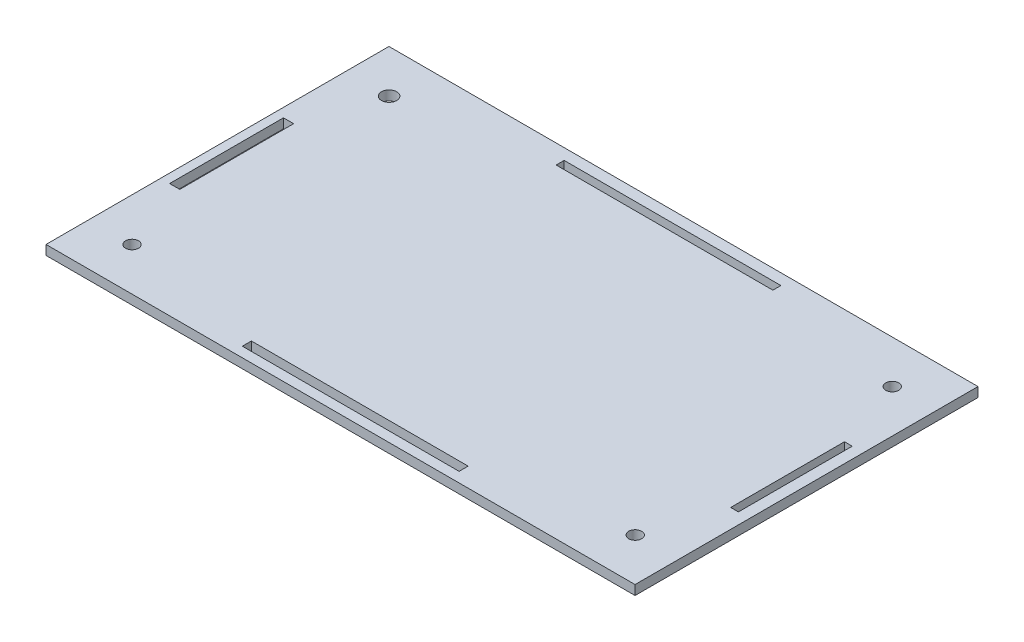
SolidWorks part; units mm, degrees
ref_plane "Front Plane" through (0, 0, 0) normal (0, 0, 1) x (1, 0, 0)
ref_plane "Top Plane" through (0, 0, 0) normal (0, 1, 0) x (1, 0, 0)
ref_plane "Right Plane" through (0, 0, 0) normal (1, 0, 0) x (0, 0, -1)
sketch "Sketch2" plane through (0, 0, 0) normal (0, 1, 0) x (1, 0, 0)
  line L15 (-5.254, 66.6261) -> (118.156, 66.6261)
  line L16 (-5.254, 66.6261) -> (-5.254, -5.2219)
  line L17 (-5.254, -5.2219) -> (118.156, -5.2219)
  line L18 (118.156, 66.6261) -> (118.156, -5.2219)
  line L19 (-1.2235, 42.6261) -> (-3.3558, 42.6261)
  line L20 (-1.2235, 42.6261) -> (-1.2235, 18.7781)
  line L21 (-1.2235, 18.7781) -> (-3.3558, 18.7781)
  line L22 (-3.3558, 42.6261) -> (-3.3558, 18.7781)
  line L23 (33.7765, 62.6261) -> (79.1865, 62.6261)
  line L24 (33.7765, 62.6261) -> (33.7765, 64.3033)
  line L25 (33.7765, 64.3033) -> (79.1865, 64.3033)
  line L26 (79.1865, 62.6261) -> (79.1865, 64.3033)
  line L27 (114.1865, 42.6261) -> (115.8073, 42.6261)
  line L28 (114.1865, 42.6261) -> (114.1865, 18.7781)
  line L29 (114.1865, 18.7781) -> (115.8073, 18.7781)
  line L30 (115.8073, 42.6261) -> (115.8073, 18.7781)
  line L31 (79.1865, -1.2219) -> (33.7765, -1.2219)
  line L32 (79.1865, -1.2219) -> (79.1865, -3.1147)
  line L33 (79.1865, -3.1147) -> (33.7765, -3.1147)
  line L34 (33.7765, -1.2219) -> (33.7765, -3.1147)
  circle A0 centre (3.7765, 3.7781) radius 1.3609
  circle A1 centre (109.1865, 3.7781) radius 1.3609
  circle A2 centre (3.7765, 57.6261) radius 1.6
  circle A3 centre (109.1865, 57.6261) radius 1.3609
  point P34 (33.7765, -2.1683)
  point P35 (114.9969, 42.6261)
  dimension "D1" = 105.41
  dimension "D2" = 53.848
  dimension "D3" = 15
  dimension "D4" = 15
  dimension "D5" = 30
  dimension "D6" = 30
  dimension "D7" = 30
  dimension "D8" = 30
  dimension "D9" = 15
  dimension "D10" = 15
extrude "Boss-Extrude1" add sketch "Sketch2" along normal blind 2
